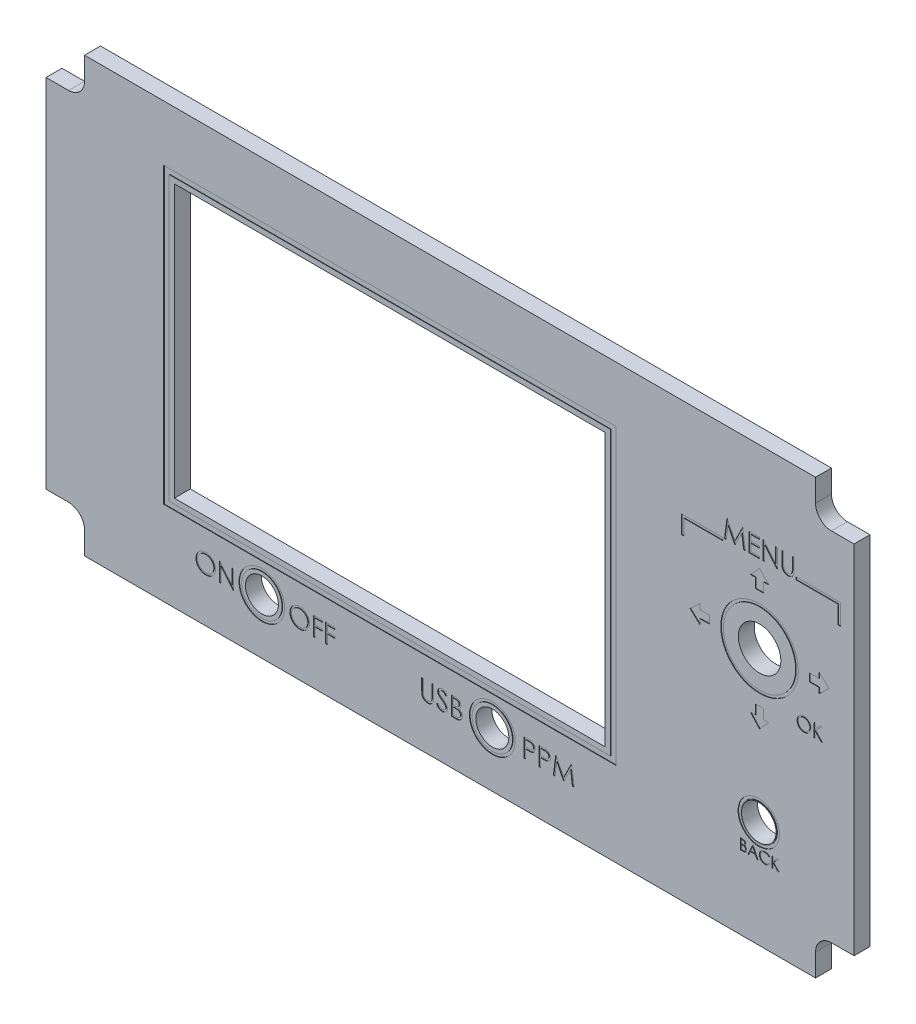
SolidWorks part; units mm, degrees
ref_plane "Plan de face" through (0, 0, 0) normal (0, 0, 1) x (1, 0, 0)
ref_plane "Plan de dessus" through (0, 0, 0) normal (0, 1, 0) x (1, 0, 0)
ref_plane "Plan de droite" through (0, 0, 0) normal (1, 0, 0) x (0, 0, -1)
sketch "Esquisse1" plane through (0, 0, 3.8) normal (0, 0, 1) x (1, 0, 0)
  line L0 (-95.6944, -23.7786) -> (-14.6944, -23.7786) construction
  line L1 (-14.6944, -23.7786) -> (-14.6944, 27.4214) construction
  line L2 (-108.6086, -31.3167) -> (5.0728, -31.3167) construction
  line L3 (-95.6944, 27.4214) -> (-95.6944, -23.7786) construction
  line L4 (-95.6944, -23.7786) -> (-14.6944, -23.7786)
  line L5 (-14.6944, -23.7786) -> (-14.6944, 27.4214)
  line L6 (-14.6944, 27.4214) -> (-95.6944, 27.4214)
  line L7 (-95.6944, 27.4214) -> (-95.6944, -23.7786)
  line L8 (-119.8323, -41.6387) -> (32.1075, -41.6387) construction
  line L9 (32.1075, 39.9055) -> (-119.8323, 39.9055) construction
  line L10 (24.869, -41.6387) -> (32.1075, -34.4002) construction
  line L12 (32.1075, 39.9055) -> (-119.8323, 39.9055) construction
  line L13 (32.1075, -41.6387) -> (32.1075, 39.9055) construction
  line L15 (-119.8323, 39.9055) -> (-119.8323, -41.6387) construction
  line L24 (-115.5896, 32.6629) -> (-119.8323, 32.6629)
  line L25 (-119.8323, 32.6629) -> (-119.8323, -34.3961)
  line L26 (-119.8323, -34.3961) -> (-115.5896, -34.3961)
  line L27 (-112.5896, -37.3961) -> (-112.5896, -41.6387)
  line L28 (-112.5896, -41.6387) -> (24.869, -41.6387)
  line L29 (24.869, -41.6387) -> (24.869, -37.4002)
  line L30 (27.869, -34.4002) -> (32.1075, -34.4002)
  line L31 (32.1075, -34.4002) -> (32.1075, 32.6629)
  line L32 (32.1075, 32.6629) -> (27.8649, 32.6629)
  line L33 (24.8649, 35.6629) -> (24.8649, 39.9055)
  line L34 (24.8649, 39.9055) -> (-112.5896, 39.9055)
  line L35 (-112.5896, 39.9055) -> (-112.5896, 35.6629)
  circle A0 centre (-35.9056, -31.3167) radius 3.1
  circle A4 centre (-79.2375, -31.3167) radius 3.1
  arc A6 (24.869, -37.4002) -> (27.869, -34.4002) centre (27.869, -37.4002) cw
  arc A7 (28.0259, -34.3961) -> (25.0259, -37.3961) centre (28.0259, -37.3961) ccw construction
  arc A8 (-115.5896, 32.6629) -> (-112.5896, 35.6629) centre (-115.5896, 35.6629) ccw
  arc A9 (-112.5896, -37.3961) -> (-115.5896, -34.3961) centre (-115.5896, -37.3961) ccw
  arc A11 (24.8649, 35.6629) -> (27.8649, 32.6629) centre (27.8649, 35.6629) ccw
  circle A28 centre (14.3452, 6.7499) radius 4
  circle A45 centre (14.1946, -21.6387) radius 3.25
  point P19 (0, 0)
  dimension "D2" = 6.5
  dimension "D1" = 6.2
  dimension "D6" = 3
  dimension "D4" = 3
  dimension "D11" = 3
  dimension "D3" = 4.2426
  dimension "D8" = 7.2426
  dimension "D9" = 7.2426
  dimension "D10" = 7.2426
extrude "Boss.-Extru.1" add sketch "Esquisse1" along normal blind 3
sketch "Gravure" plane through (0, 0, 6.8) normal (0, 0, 1) x (1, 0, 0)
  line L0 (-0.3763, 21.3599) -> (-0.3763, 17.9616)
  line L1 (14.3452, 6.7499) -> (14.3452, 16.1393) construction
  line L2 (13.6084, 16.1393) -> (15.082, 16.1393)
  line L3 (13.6084, 16.1393) -> (13.6084, 17.9616)
  line L4 (13.6084, 17.9616) -> (12.6237, 17.9616)
  line L5 (12.6237, 17.9616) -> (14.3452, 19.8356)
  line L6 (14.3452, 19.8356) -> (16.0668, 17.9616)
  line L7 (16.0668, 17.9616) -> (15.082, 17.9616)
  line L8 (15.082, 17.9616) -> (15.082, 16.1393)
  line L9 (14.3452, 6.7499) -> (17.3937, 6.7499) construction
  line L10 (25.557, 6.013) -> (23.7347, 6.013)
  line L11 (25.557, 5.0283) -> (25.557, 6.013)
  line L12 (27.431, 6.7499) -> (25.557, 5.0283)
  line L13 (25.557, 8.4714) -> (27.431, 6.7499)
  line L14 (25.557, 7.4867) -> (25.557, 8.4714)
  line L15 (23.7347, 7.4867) -> (25.557, 7.4867)
  line L16 (23.7347, 7.4867) -> (23.7347, 6.013)
  line L17 (13.6084, -4.4619) -> (13.6084, -2.6396)
  line L18 (12.6237, -4.4619) -> (13.6084, -4.4619)
  line L19 (14.3452, -6.3359) -> (12.6237, -4.4619)
  line L20 (16.0668, -4.4619) -> (14.3452, -6.3359)
  line L21 (15.082, -4.4619) -> (16.0668, -4.4619)
  line L22 (15.082, -2.6396) -> (15.082, -4.4619)
  line L23 (15.082, -2.6396) -> (13.6084, -2.6396)
  line L24 (3.1335, 7.4867) -> (4.9558, 7.4867)
  line L25 (3.1335, 8.4714) -> (3.1335, 7.4867)
  line L26 (1.2595, 6.7499) -> (3.1335, 8.4714)
  line L27 (3.1335, 5.0283) -> (1.2595, 6.7499)
  line L28 (3.1335, 6.013) -> (3.1335, 5.0283)
  line L29 (4.9558, 6.013) -> (3.1335, 6.013)
  line L30 (4.9558, 6.013) -> (4.9558, 7.4867)
  line L31 (-96.6944, 28.4214) -> (-13.6944, 28.4214)
  line L32 (7.4858, 21.3599) -> (21.2046, 21.3599) construction
  line L33 (14.3452, 19.8356) -> (14.3452, 21.3599) construction
  line L34 (-13.6944, 28.4214) -> (-13.6944, -24.7786)
  line L35 (10.4737, -27.822) -> (18.2168, -27.822) construction
  line L36 (7.4858, 21.3599) -> (-0.3763, 21.3599)
  line L37 (-74.2371, -33.2481) -> (-67.4657, -33.2481) construction
  line L38 (21.2046, -2.6396) -> (25.557, -2.6396) construction
  line L39 (21.2046, 21.3599) -> (29.0668, 21.3599)
  line L40 (29.0668, 21.3599) -> (29.0668, 17.9616)
  line L41 (-91.913, -33.2481) -> (-84.8778, -33.2481) construction
  line L42 (-49.6295, -33.2481) -> (-41.3164, -33.2481) construction
  line L43 (-30.4453, -33.2481) -> (-24.3703, -33.2481) construction
  line L44 (7.4858, 20.8599) -> (0.1237, 20.8599)
  line L45 (0.1237, 20.8599) -> (0.1237, 17.9616)
  line L46 (21.2046, 21.8599) -> (29.5668, 21.8599)
  line L47 (29.5668, 21.8599) -> (29.5668, 17.9616)
  line L48 (-0.3763, 17.9616) -> (0.1237, 17.9616)
  line L49 (7.4858, 21.3599) -> (7.4858, 20.8599)
  line L50 (21.2046, 21.8599) -> (21.2046, 21.3599)
  line L51 (29.0668, 17.9616) -> (29.5668, 17.9616)
  line L53 (-95.6944, 27.4214) -> (-14.6944, 27.4214) construction
  line L54 (-95.6944, 27.4214) -> (-95.6944, -23.7786) construction
  line L55 (-95.6944, -23.7786) -> (-14.6944, -23.7786) construction
  line L56 (-14.6944, 27.4214) -> (-14.6944, -23.7786) construction
  line L57 (-96.6944, -24.7786) -> (-13.6944, -24.7786)
  line L58 (-96.6944, 28.4214) -> (-96.6944, -24.7786)
  line L71 (-97.6944, 29.4214) -> (-12.6944, 29.4214)
  line L72 (-12.6944, 29.4214) -> (-12.6944, -25.7786)
  line L73 (-97.6944, -25.7786) -> (-12.6944, -25.7786)
  line L74 (-97.6944, 29.4214) -> (-97.6944, -25.7786)
  circle A0 centre (14.3452, 6.7499) radius 6.7956
  circle A1 centre (14.3452, 6.7499) radius 7.2956
  circle A2 centre (-79.2375, -31.3167) radius 3.8
  circle A4 centre (14.1946, -21.6387) radius 3.3928
  circle A5 centre (14.1946, -21.6387) radius 3.8928
  circle A6 centre (-79.2375, -31.3167) radius 4.3
  circle A7 centre (-35.9056, -31.3167) radius 3.8
  circle A8 centre (-35.9056, -31.3167) radius 4.3
  circle A9 centre (14.1946, -21.6387) radius 3.25 construction
  text T0 "MENU"
  text T1 "BACK" font "Century Gothic" height 2
  text T2 "OK" font "Century Gothic" height 2.5
  text T3 "ON"
  text T4 "OFF"
  text T5 "USB"
  text T6 "PPM"
  point P7 (14.3452, 16.1393)
  point P38 (14.3452, 6.7499)
  point P39 (14.3452, 21.3599)
  point P77 (0, 0)
  point P85 (0, 0)
  point P86 (0, 0)
  point P87 (0, 0)
  point P88 (0, 0)
  point P89 (0, 0)
  point P90 (10.4737, -26.4388)
  point P91 (14.1946, -18.5345)
  point P92 (0, 0)
  point P93 (0, 0)
  dimension "D1" = 0.5
  dimension "D5" = 0.5
  dimension "D3" = 13
  dimension "D4" = 13
  dimension "D6" = 0.5
  dimension "D7" = 0.5
  dimension "D8" = 0.5
  dimension "D9" = 1
  dimension "D10" = 1
  dimension "D2" = 4
extrude "Enlèv. mat.-Extru.1" cut sketch "Gravure" against normal blind 0.1
